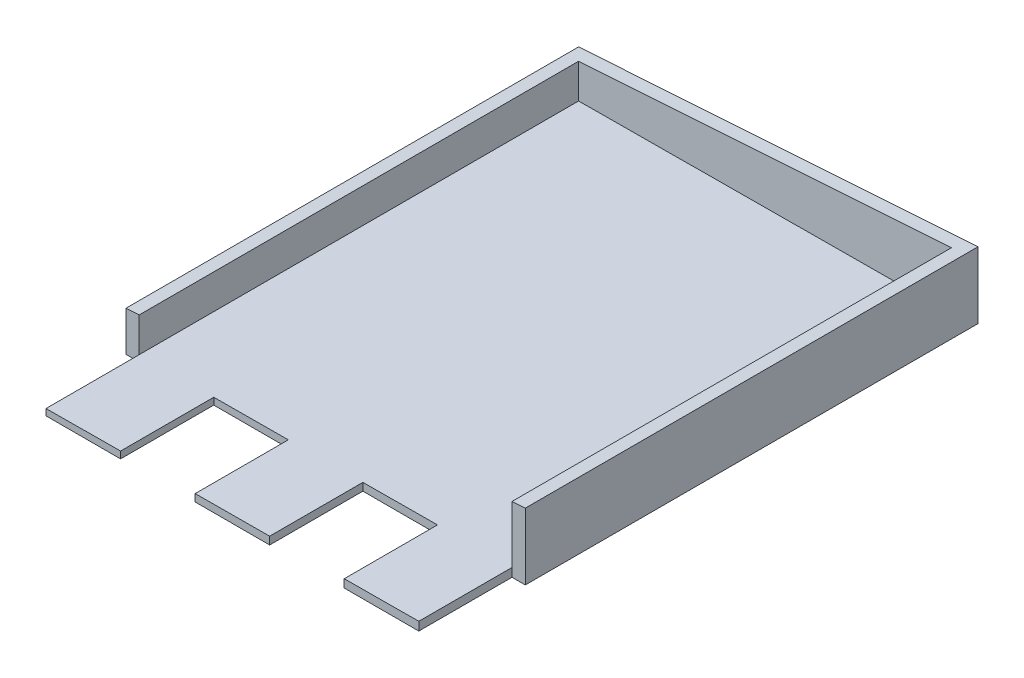
SolidWorks part; units mm, degrees
ref_plane "Front Plane" through (0, 0, 0) normal (0, 0, 1) x (1, 0, 0)
ref_plane "Top Plane" through (0, 0, 0) normal (0, 1, 0) x (1, 0, 0)
ref_plane "Right Plane" through (0, 0, 0) normal (1, 0, 0) x (0, 0, -1)
sketch "Sketch1" plane through (0, 0, 0) normal (0, 0, 1) x (1, 0, 0)
  line L0 (0, 0) -> (0, -15)
  line L1 (0, -15) -> (150, -15)
  line L2 (150, -15) -> (150, 10)
  line L9 (0, 0) -> (150, 10)
  dimension "D1" = 15
  dimension "D2" = 90
  dimension "D3" = 150
  dimension "D4" = 25
extrude "Boss-Extrude1" add sketch "Sketch1" along normal blind 170
sketch "Sketch2" plane through (0, 0, 170) normal (0, 0, 1) x (1, 0, 0)
  line L0 (5, 0.3333) -> (5, -12.6)
  line L1 (150, 10) -> (0, 0) construction
  line L2 (5, -12.6) -> (145, -11.8)
  line L3 (145, -11.8) -> (145, 9.6667)
  line L4 (145, 9.6667) -> (5, 0.3333)
  line L5 (0, -15) -> (150, -15) construction
  line L6 (0, 0) -> (0, -15) construction
  dimension "D1" = 2.4
  dimension "D2" = 3.2
  dimension "D3" = 140
  dimension "D4" = 5
extrude "Cut-Extrude1" cut sketch "Sketch2" against normal blind 165
sketch "Sketch3" plane through (0, 0, 170) normal (0, 0, 1) x (1, 0, 0)
  line L7 (145, -11.8) -> (145, -15)
  line L8 (0, -15) -> (150, -15) construction
  line L9 (145, -15) -> (117, -15)
  line L10 (117, -15) -> (117, -11.96)
  line L11 (5, -12.6) -> (145, -11.8) construction
  line L12 (117, -11.96) -> (145, -11.8)
  dimension "D1" = 28
extrude "Boss-Extrude2" add sketch "Sketch3" along normal blind 35
sketch "Sketch4" plane through (0, 0, 170) normal (0, 0, 1) x (1, 0, 0)
  line L0 (89, -12.12) -> (89, -15)
  line L1 (5, -12.6) -> (117, -11.96) construction
  line L2 (0, -15) -> (117, -15) construction
  line L3 (89, -15) -> (61, -15)
  line L4 (61, -15) -> (61, -12.28)
  line L5 (61, -12.28) -> (89, -12.12)
  line L6 (5, -12.6) -> (5, -15)
  line L7 (5, -15) -> (33, -15)
  line L8 (33, -15) -> (33, -12.44)
  line L9 (5, -12.6) -> (145, -11.8) construction
  line L10 (33, -12.44) -> (5, -12.6)
  dimension "D1" = 28
  dimension "D2" = 28
  dimension "D3" = 28
extrude "Boss-Extrude3" add sketch "Sketch4" along normal blind 35
